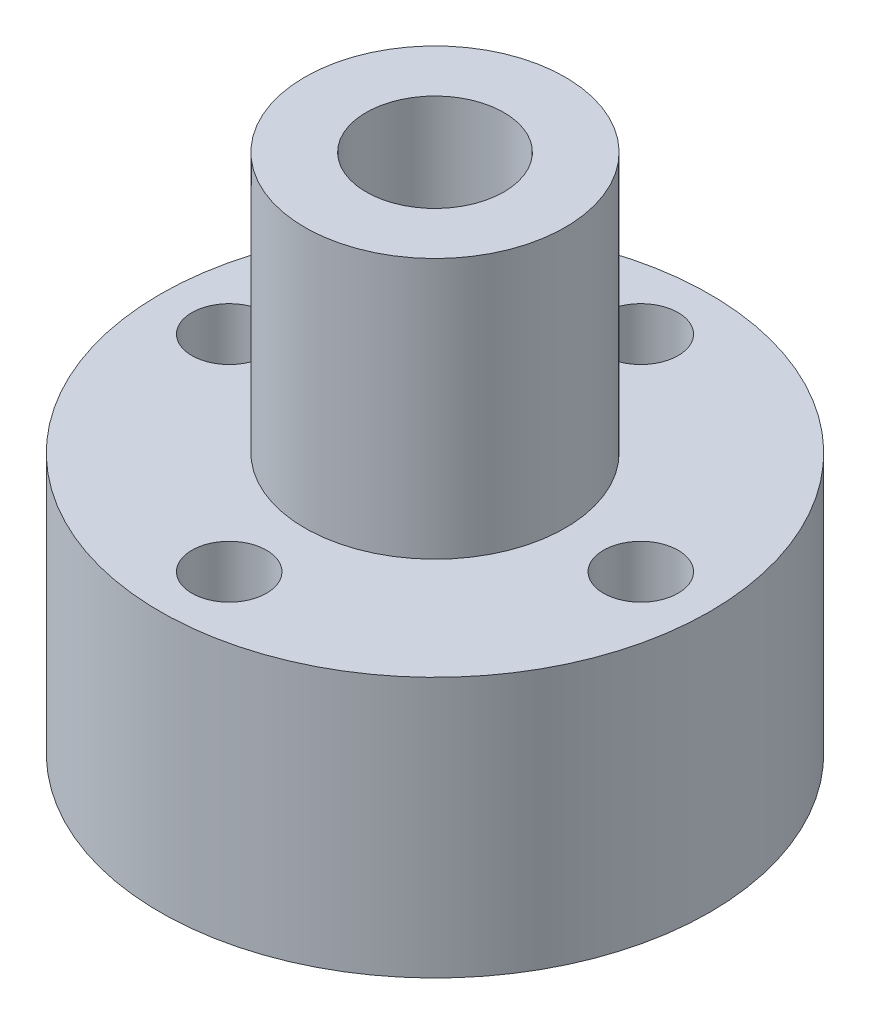
SolidWorks part; units mm, degrees
material "Brass"
ref_plane "Front Plane" through (0, 0, 0) normal (0, 0, 1) x (1, 0, 0)
ref_plane "Top Plane" through (0, 0, 0) normal (0, 1, 0) x (1, 0, 0)
ref_plane "Right Plane" through (0, 0, 0) normal (1, 0, 0) x (0, 0, -1)
sketch "Sketch1" plane through (0, 0, 0) normal (0, 0, 1) x (1, 0, 0)
  line L0 (0, 0) -> (19, 0)
  line L1 (19, 0) -> (19, 18)
  line L2 (19, 18) -> (9, 18)
  line L3 (9, 18) -> (9, 36)
  line L4 (9, 36) -> (0, 36)
  line L5 (0, 36) -> (0, 0)
  dimension "D1" = 19
  dimension "D2" = 9
  dimension "D3" = 18
  dimension "D4" = 18
revolve "Revolve1" add sketch "Sketch1" angle 360 about L5
sketch "Sketch2" plane through (0, 0, 0) normal (0, -1, 0) x (1, 0, 0)
  circle A0 centre (0, 0) radius 4.7625
  dimension "D1" = 9.525
extrude "Cut-Extrude1" cut sketch "Sketch2" against normal up to next
sketch "Sketch3" plane through (0, 0, 0) normal (0, -1, 0) x (1, 0, 0)
  line L0 (-16.805, 0) -> (16.805, 0) construction
  line L1 (0, 16.805) -> (0, -16.805) construction
  circle A0 centre (0, 14.225) radius 2.58
  circle A1 centre (14.225, 0) radius 2.58
  circle A2 centre (0, -14.225) radius 2.58
  circle A3 centre (-14.225, 0) radius 2.58
  point P3 (0, 0)
  point P10 (0, 0)
  dimension "D1" = 5.16
  dimension "D2" = 33.61
extrude "Cut-Extrude2" cut sketch "Sketch3" against normal through all
